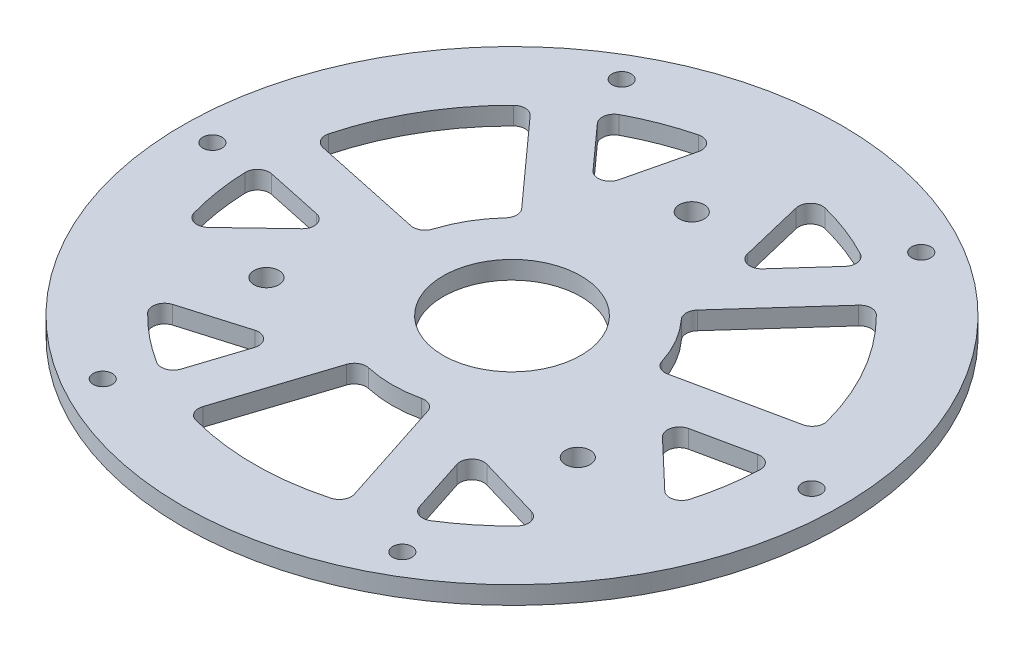
SolidWorks part; units mm, degrees
ref_plane "前视基准面" through (0, 0, 0) normal (0, 0, 1) x (1, 0, 0)
ref_plane "上视基准面" through (0, 0, 0) normal (0, 1, 0) x (1, 0, 0)
ref_plane "右视基准面" through (0, 0, 0) normal (1, 0, 0) x (0, 0, -1)
sketch "草图1" plane through (0, 0, 0) normal (0, 1, 0) x (1, 0, 0)
  line L0 (0, 0) -> (25, 43.3013) construction
  line L1 (0, 30) -> (0, 0) construction
  line L2 (0, 0) -> (-9.9593, 5.75) construction
  line L5 (-13.3826, 14.8629) -> (-28.7726, 31.9552)
  line L6 (-17.3205, 10) -> (-76.6736, 44.2675) construction
  line L7 (-19.563, 4.1582) -> (-42.0603, 8.9402)
  line L8 (19.563, 4.1582) -> (42.0603, 8.9402)
  line L9 (13.3826, 14.8629) -> (28.7726, 31.9552)
  line L10 (-6.1803, -19.0211) -> (-13.2877, -40.8954)
  line L11 (6.1803, -19.0211) -> (13.2877, -40.8954)
  circle A0 centre (0, 0) radius 11.5
  circle A1 centre (0, 30) radius 2.075
  circle A2 centre (25.9808, -15) radius 2.075
  circle A3 centre (-25.9808, -15) radius 2.075
  circle A6 centre (0, 0) radius 50 construction
  circle A7 centre (25, 43.3013) radius 1.6
  circle A8 centre (50, 0) radius 1.6
  circle A9 centre (25, -43.3013) radius 1.6
  circle A10 centre (-25, -43.3013) radius 1.6
  circle A11 centre (-50, 0) radius 1.6
  circle A12 centre (-25, 43.3013) radius 1.6
  circle A13 centre (0, 0) radius 55
  arc A14 (-42.0603, 8.9402) -> (-28.7726, 31.9552) centre (0, 0) cw
  arc A15 (-19.563, 4.1582) -> (-13.3826, 14.8629) centre (0, 0) cw
  arc A16 (28.7726, 31.9552) -> (42.0603, 8.9402) centre (0, 0) cw
  arc A17 (13.3826, 14.8629) -> (19.563, 4.1582) centre (0, 0) cw
  arc A18 (13.2877, -40.8954) -> (-13.2877, -40.8954) centre (0, 0) cw
  arc A19 (6.1803, -19.0211) -> (-6.1803, -19.0211) centre (0, 0) cw
  point P11 (0, 0)
  point P26 (0, 0)
  point P42 (0, 0)
  dimension "D2" = 4.15
  dimension "D3" = 3
  dimension "D4" = 23
  dimension "D6" = 30
  dimension "D7" = 6
  dimension "D5" = 43
  dimension "D8" = 3.2
  dimension "D9" = 50
  dimension "D10" = 110
  dimension "D11" = 20
  dimension "D1" = 30
  dimension "D12" = 3
  dimension "D13" = 18
extrude "凸台-拉伸1" add sketch "草图1" along normal blind 3
sketch "草图3" plane through (0, 3, 0) normal (0, 1, 0) x (1, 0, 0)
  line L0 (-20.6607, 34.9018) -> (-14.1596, 27.6816)
  line L1 (-13.3826, 14.8629) -> (-28.7726, 31.9552) construction
  line L2 (0, 0) -> (0, 69.1288) construction
  line L3 (-8.1442, 39.2706) -> (-10.729, 28.5511)
  line L4 (8.1442, 39.2706) -> (10.729, 28.5511)
  line L5 (20.6607, 34.9018) -> (14.1596, 27.6816)
  line L6 (40.5562, 0.4418) -> (31.0528, -1.5783)
  line L7 (38.0815, -12.5822) -> (30.0905, -4.9839)
  line L8 (29.9372, -26.6884) -> (19.3614, -23.5671)
  line L9 (19.8955, -35.3436) -> (16.8932, -26.1034)
  line L10 (-19.8955, -35.3436) -> (-16.8932, -26.1034)
  line L11 (-29.9372, -26.6884) -> (-19.3614, -23.5671)
  line L12 (-38.0815, -12.5822) -> (-30.0905, -4.9839)
  line L13 (-40.5562, 0.4418) -> (-31.0528, -1.5783)
  arc A0 (-20.1097, 38.0079) -> (-10.5806, 41.6779) centre (0, 0) cw
  arc A1 (-28.7726, 31.9552) -> (-42.0603, 8.9402) centre (0, 0) ccw construction
  arc A2 (20.1097, 38.0079) -> (10.5806, 41.6779) centre (0, 0) ccw
  arc A3 (42.9707, -1.5884) -> (41.3845, -11.6759) centre (0, 0) cw
  arc A4 (22.8609, -36.4195) -> (30.8038, -30.0021) centre (0, 0) ccw
  arc A5 (-22.8609, -36.4195) -> (-30.8038, -30.0021) centre (0, 0) cw
  arc A6 (-42.9707, -1.5884) -> (-41.3845, -11.6759) centre (0, 0) ccw
  arc A7 (-30.0905, -4.9839) -> (-31.0528, -1.5783) centre (-31.4686, -3.5345) ccw
  arc A8 (-38.0815, -12.5822) -> (-41.3845, -11.6759) centre (-39.4596, -11.1328) cw
  arc A9 (-40.5562, 0.4418) -> (-42.9707, -1.5884) centre (-40.972, -1.5145) ccw
  arc A10 (-29.9372, -26.6884) -> (-30.8038, -30.0021) centre (-29.3711, -28.6066) ccw
  arc A11 (-16.8932, -26.1034) -> (-19.3614, -23.5671) centre (-18.7953, -25.4853) ccw
  arc A12 (-19.8955, -35.3436) -> (-22.8609, -36.4195) centre (-21.7976, -34.7255) cw
  arc A13 (19.3614, -23.5671) -> (16.8932, -26.1034) centre (18.7953, -25.4853) ccw
  arc A14 (29.9372, -26.6884) -> (30.8038, -30.0021) centre (29.3711, -28.6066) cw
  arc A15 (19.8955, -35.3436) -> (22.8609, -36.4195) centre (21.7976, -34.7255) ccw
  arc A16 (10.729, 28.5511) -> (14.1596, 27.6816) centre (12.6733, 29.0199) ccw
  arc A17 (10.5806, 41.6779) -> (8.1442, 39.2706) centre (10.0885, 39.7394) ccw
  arc A18 (20.1097, 38.0079) -> (20.6607, 34.9018) centre (19.1744, 36.2401) cw
  arc A19 (38.0815, -12.5822) -> (41.3845, -11.6759) centre (39.4596, -11.1328) ccw
  arc A20 (31.0528, -1.5783) -> (30.0905, -4.9839) centre (31.4686, -3.5345) ccw
  arc A21 (40.5562, 0.4418) -> (42.9707, -1.5884) centre (40.972, -1.5145) cw
  arc A22 (-10.5806, 41.6779) -> (-8.1442, 39.2706) centre (-10.0885, 39.7394) cw
  arc A23 (-14.1596, 27.6816) -> (-10.729, 28.5511) centre (-12.6733, 29.0199) ccw
  arc A24 (-20.6607, 34.9018) -> (-20.1097, 38.0079) centre (-19.1744, 36.2401) cw
  point P29 (0, 0)
  point P47 (11.619, 24.86)
  point P50 (7.3997, 42.3585)
  point P53 (22.3251, 36.7504)
  point P62 (-7.3997, 42.3585)
  point P65 (-11.619, 24.86)
  point P68 (-22.3251, 36.7504)
  dimension "D1" = 8
  dimension "D3" = 18
  dimension "D5" = 2
  dimension "D2" = 16
  dimension "D4" = 3
extrude "切除-拉伸1" cut sketch "草图3" against normal up to next
fillet "圆角1" radius 2 12 edges at (-13.2877, 1.5, 40.8954) (13.2877, 1.5, 40.8954) (6.1803, 1.5, 19.0211) (-6.1803, 1.5, 19.0211) (28.7726, 1.5, -31.9552) (13.3826, 1.5, -14.8629) (19.563, 1.5, -4.1582) (42.0603, 1.5, -8.9402) (-13.3826, 1.5, -14.8629) (-19.563, 1.5, -4.1582) (-28.7726, 1.5, -31.9552) (-42.0603, 1.5, -8.9402)
